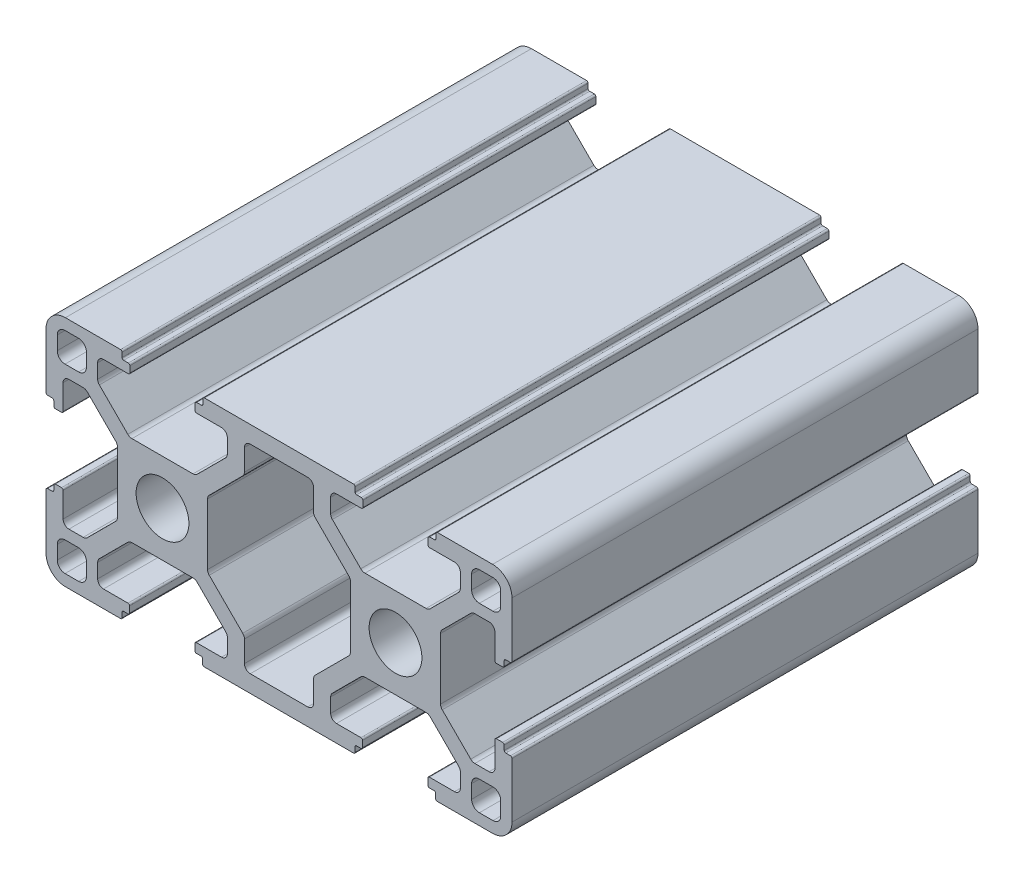
SolidWorks part; units mm, degrees
material "6063-T5"
ref_plane "Front Plane" through (0, 0, 0) normal (0, 0, 1) x (1, 0, 0)
ref_plane "Top Plane" through (0, 0, 0) normal (0, 1, 0) x (1, 0, 0)
ref_plane "Right Plane" through (0, 0, 0) normal (1, 0, 0) x (0, 0, -1)
sketch "Sketch1" plane through (0, 0, 0) normal (0, 0, 1) x (1, 0, 0)
  line L0 (2.5, 0) -> (9.6, 0)
  line L1 (60, 2.5) -> (60, 9.6)
  line L2 (57.5, 30) -> (50.4, 30)
  line L3 (0, 27.5) -> (0, 20.4)
  line L4 (21.0197, 10.536) -> (25.3303, 6.2253)
  line L5 (19.464, 21.0197) -> (23.1303, 24.686)
  line L6 (19.464, 8.9803) -> (23.1303, 5.314)
  line L7 (21.0197, 19.464) -> (25.3303, 23.7747)
  line L8 (11.0663, 9.2) -> (18.9337, 9.2)
  line L9 (9.2, 18.9337) -> (9.2, 11.0663)
  line L10 (41.0663, 9.2) -> (48.9337, 9.2)
  line L11 (40.536, 21.0197) -> (36.8697, 24.686)
  line L12 (50.8, 18.9337) -> (50.8, 11.0663)
  line L13 (38.9803, 10.536) -> (34.6697, 6.2253)
  line L14 (5.314, 23.1303) -> (8.9803, 19.464)
  line L15 (6.8697, 24.686) -> (10.536, 21.0197)
  line L16 (40.536, 8.9803) -> (36.8697, 5.314)
  line L17 (38.9803, 19.464) -> (34.6697, 23.7747)
  line L18 (5.314, 6.8697) -> (8.9803, 10.536)
  line L19 (6.8697, 5.314) -> (10.536, 8.9803)
  line L20 (36.65, 25.2163) -> (36.65, 27.05)
  line L21 (4.7837, 23.35) -> (2.95, 23.35)
  line L22 (4.7837, 6.65) -> (2.95, 6.65)
  line L23 (53.35, 25.2163) -> (53.35, 27.05)
  line L24 (53.1303, 24.686) -> (49.464, 21.0197)
  line L25 (54.686, 23.1303) -> (51.0197, 19.464)
  line L26 (54.686, 6.8697) -> (51.0197, 10.536)
  line L27 (53.1303, 5.314) -> (49.464, 8.9803)
  line L28 (11.0663, 20.8) -> (18.9337, 20.8)
  line L29 (41.0663, 20.8) -> (48.9337, 20.8)
  line L30 (20.8, 18.9337) -> (20.8, 11.0663)
  line L31 (39.2, 18.9337) -> (39.2, 11.0663)
  line L32 (6.65, 4.7837) -> (6.65, 2.95)
  line L33 (6.65, 27.05) -> (6.65, 25.2163)
  line L34 (23.35, 27.05) -> (23.35, 25.2163)
  line L35 (55.2163, 23.35) -> (57.05, 23.35)
  line L36 (55.2163, 6.65) -> (57.05, 6.65)
  line L37 (23.35, 4.7837) -> (23.35, 2.95)
  line L38 (36.65, 4.7837) -> (36.65, 2.95)
  line L39 (53.35, 4.7837) -> (53.35, 2.95)
  line L40 (34.45, 24.305) -> (34.45, 27.05)
  line L41 (25.55, 24.305) -> (25.55, 27.05)
  line L42 (25.55, 5.695) -> (25.55, 2.95)
  line L43 (34.45, 5.695) -> (34.45, 2.95)
  line L44 (26.3, 27.8) -> (33.7, 27.8)
  line L45 (7.4, 27.8) -> (10.6, 27.8)
  line L46 (7.4, 2.2) -> (10.5556, 2.2)
  line L47 (2.2, 22.6) -> (2.2, 19.4)
  line L48 (57.8, 22.6) -> (57.8, 19.4)
  line L49 (37.4, 27.8) -> (40.6, 27.8)
  line L50 (26.3, 2.2) -> (33.7, 2.2)
  line L51 (37.4, 2.2) -> (40.5556, 2.2)
  line L52 (9.6, 30) -> (2.5, 30)
  line L53 (19.2, 28) -> (19.2, 28.8)
  line L54 (10.7556, 2) -> (10.7556, 1.2)
  line L55 (10.8, 28) -> (10.8, 28.8)
  line L56 (19.4, 27.8) -> (22.6, 27.8)
  line L57 (40.8, 28) -> (40.8, 28.8)
  line L58 (19.1556, 2) -> (19.1556, 1.2)
  line L59 (20.3556, 0) -> (39.6, 0)
  line L60 (19.3556, 2.2) -> (22.6, 2.2)
  line L61 (49.1556, 2) -> (49.1556, 1.2)
  line L62 (40.7556, 2) -> (40.7556, 1.2)
  line L63 (49.2, 28) -> (49.2, 28.8)
  line L64 (49.4, 27.8) -> (52.6, 27.8)
  line L65 (39.6, 30) -> (20.4, 30)
  line L66 (50.3556, 0) -> (57.5, 0)
  line L67 (49.3556, 2.2) -> (52.6, 2.2)
  line L68 (4.2, 24.8) -> (2.45, 24.8)
  line L69 (2, 19.2) -> (1.2, 19.2)
  line L70 (58, 19.2) -> (58.8, 19.2)
  line L71 (2, 10.8) -> (1.2, 10.8)
  line L72 (0, 9.6) -> (0, 2.5)
  line L73 (2.2, 10.6) -> (2.2, 7.4)
  line L74 (5.2, 27.55) -> (5.2, 25.8)
  line L75 (58, 10.8) -> (58.8, 10.8)
  line L76 (60, 20.4) -> (60, 27.5)
  line L77 (57.8, 10.6) -> (57.8, 7.4)
  line L78 (55.8, 28.55) -> (57.55, 28.55)
  line L79 (58.55, 4.2) -> (58.55, 2.45)
  line L80 (4.2, 28.55) -> (2.45, 28.55)
  line L81 (1.45, 25.8) -> (1.45, 27.55)
  line L82 (55.8, 24.8) -> (57.55, 24.8)
  line L83 (1.45, 4.2) -> (1.45, 2.45)
  line L84 (2.45, 5.2) -> (4.2, 5.2)
  line L85 (5.2, 2.45) -> (5.2, 4.2)
  line L86 (54.8, 2.45) -> (54.8, 4.2)
  line L87 (55.8, 5.2) -> (57.55, 5.2)
  line L88 (4.2, 1.45) -> (2.45, 1.45)
  line L89 (58.55, 27.55) -> (58.55, 25.8)
  line L90 (19.4, 29) -> (20, 29)
  line L91 (54.8, 25.8) -> (54.8, 27.55)
  line L92 (57.55, 1.45) -> (55.8, 1.45)
  line L93 (9.8, 29.8) -> (9.8, 29.2)
  line L94 (10, 29) -> (10.6, 29)
  line L95 (20.2, 29.2) -> (20.2, 29.8)
  line L96 (9.8, 0.2) -> (9.8, 0.8)
  line L97 (0.2, 20.2) -> (0.8, 20.2)
  line L98 (1, 20) -> (1, 19.4)
  line L99 (1, 10.6) -> (1, 10)
  line L100 (0.8, 9.8) -> (0.2, 9.8)
  line L101 (10, 1) -> (10.5556, 1)
  line L102 (19.3556, 1) -> (19.9556, 1)
  line L103 (20.1556, 0.8) -> (20.1556, 0.2)
  line L104 (50.2, 29.2) -> (50.2, 29.8)
  line L105 (49.4, 29) -> (50, 29)
  line L106 (39.8, 29.8) -> (39.8, 29.2)
  line L107 (40, 29) -> (40.6, 29)
  line L108 (50.1556, 0.8) -> (50.1556, 0.2)
  line L109 (49.3556, 1) -> (49.9556, 1)
  line L110 (40, 1) -> (40.5556, 1)
  line L111 (39.8, 0.2) -> (39.8, 0.8)
  line L112 (59.8, 20.2) -> (59.2, 20.2)
  line L113 (59, 20) -> (59, 19.4)
  line L114 (59, 10.6) -> (59, 10)
  line L115 (59.2, 9.8) -> (59.8, 9.8)
  circle A0 centre (15, 15) radius 3.4
  circle A1 centre (45, 15) radius 3.4
  arc A2 (55.8, 1.45) -> (54.8, 2.45) centre (55.8, 2.45) cw
  arc A3 (57.55, 1.45) -> (58.55, 2.45) centre (57.55, 2.45) ccw
  arc A4 (57.55, 5.2) -> (58.55, 4.2) centre (57.55, 4.2) cw
  arc A5 (54.8, 4.2) -> (55.8, 5.2) centre (55.8, 4.2) cw
  arc A6 (55.8, 24.8) -> (54.8, 25.8) centre (55.8, 25.8) cw
  arc A7 (58.55, 25.8) -> (57.55, 24.8) centre (57.55, 25.8) cw
  arc A8 (57.55, 28.55) -> (58.55, 27.55) centre (57.55, 27.55) cw
  arc A9 (55.8, 28.55) -> (54.8, 27.55) centre (55.8, 27.55) ccw
  arc A10 (4.2, 5.2) -> (5.2, 4.2) centre (4.2, 4.2) cw
  arc A11 (4.2, 1.45) -> (5.2, 2.45) centre (4.2, 2.45) ccw
  arc A12 (2.45, 1.45) -> (1.45, 2.45) centre (2.45, 2.45) cw
  arc A13 (2.45, 5.2) -> (1.45, 4.2) centre (2.45, 4.2) ccw
  arc A14 (2.45, 24.8) -> (1.45, 25.8) centre (2.45, 25.8) cw
  arc A15 (4.2, 28.55) -> (5.2, 27.55) centre (4.2, 27.55) cw
  arc A16 (4.2, 24.8) -> (5.2, 25.8) centre (4.2, 25.8) ccw
  arc A17 (2.45, 28.55) -> (1.45, 27.55) centre (2.45, 27.55) ccw
  arc A18 (60, 27.5) -> (57.5, 30) centre (57.5, 27.5) ccw
  arc A19 (57.5, 0) -> (60, 2.5) centre (57.5, 2.5) ccw
  arc A20 (2.5, 0) -> (0, 2.5) centre (2.5, 2.5) cw
  arc A21 (2.5, 30) -> (0, 27.5) centre (2.5, 27.5) ccw
  arc A22 (53.35, 4.7837) -> (53.1303, 5.314) centre (52.6, 4.7837) ccw
  arc A23 (52.6, 2.2) -> (53.35, 2.95) centre (52.6, 2.95) ccw
  arc A24 (36.65, 2.95) -> (37.4, 2.2) centre (37.4, 2.95) ccw
  arc A25 (36.65, 4.7837) -> (36.8697, 5.314) centre (37.4, 4.7837) cw
  arc A26 (48.9337, 9.2) -> (49.464, 8.9803) centre (48.9337, 8.45) cw
  arc A27 (41.0663, 9.2) -> (40.536, 8.9803) centre (41.0663, 8.45) ccw
  arc A28 (57.8, 7.4) -> (57.05, 6.65) centre (57.05, 7.4) cw
  arc A29 (55.2163, 6.65) -> (54.686, 6.8697) centre (55.2163, 7.4) cw
  arc A30 (50.8, 11.0663) -> (51.0197, 10.536) centre (51.55, 11.0663) ccw
  arc A31 (50.8, 18.9337) -> (51.0197, 19.464) centre (51.55, 18.9337) cw
  arc A32 (55.2163, 23.35) -> (54.686, 23.1303) centre (55.2163, 22.6) ccw
  arc A33 (57.8, 22.6) -> (57.05, 23.35) centre (57.05, 22.6) ccw
  arc A34 (52.6, 27.8) -> (53.35, 27.05) centre (52.6, 27.05) cw
  arc A35 (53.35, 25.2163) -> (53.1303, 24.686) centre (52.6, 25.2163) cw
  arc A36 (48.9337, 20.8) -> (49.464, 21.0197) centre (48.9337, 21.55) ccw
  arc A37 (41.0663, 20.8) -> (40.536, 21.0197) centre (41.0663, 21.55) cw
  arc A38 (36.65, 25.2163) -> (36.8697, 24.686) centre (37.4, 25.2163) ccw
  arc A39 (36.65, 27.05) -> (37.4, 27.8) centre (37.4, 27.05) cw
  arc A40 (23.35, 2.95) -> (22.6, 2.2) centre (22.6, 2.95) cw
  arc A41 (23.35, 4.7837) -> (23.1303, 5.314) centre (22.6, 4.7837) ccw
  arc A42 (18.9337, 9.2) -> (19.464, 8.9803) centre (18.9337, 8.45) cw
  arc A43 (11.0663, 9.2) -> (10.536, 8.9803) centre (11.0663, 8.45) ccw
  arc A44 (6.65, 4.7837) -> (6.8697, 5.314) centre (7.4, 4.7837) cw
  arc A45 (7.4, 2.2) -> (6.65, 2.95) centre (7.4, 2.95) cw
  arc A46 (34.45, 27.05) -> (33.7, 27.8) centre (33.7, 27.05) ccw
  arc A47 (34.45, 24.305) -> (34.6697, 23.7747) centre (35.2, 24.305) ccw
  arc A48 (39.2, 18.9337) -> (38.9803, 19.464) centre (38.45, 18.9337) ccw
  arc A49 (39.2, 11.0663) -> (38.9803, 10.536) centre (38.45, 11.0663) cw
  arc A50 (34.45, 5.695) -> (34.6697, 6.2253) centre (35.2, 5.695) cw
  arc A51 (34.45, 2.95) -> (33.7, 2.2) centre (33.7, 2.95) cw
  arc A52 (25.55, 2.95) -> (26.3, 2.2) centre (26.3, 2.95) ccw
  arc A53 (25.55, 5.695) -> (25.3303, 6.2253) centre (24.8, 5.695) ccw
  arc A54 (20.8, 11.0663) -> (21.0197, 10.536) centre (21.55, 11.0663) ccw
  arc A55 (20.8, 18.9337) -> (21.0197, 19.464) centre (21.55, 18.9337) cw
  arc A56 (25.55, 24.305) -> (25.3303, 23.7747) centre (24.8, 24.305) cw
  arc A57 (25.55, 27.05) -> (26.3, 27.8) centre (26.3, 27.05) cw
  arc A58 (23.35, 27.05) -> (22.6, 27.8) centre (22.6, 27.05) ccw
  arc A59 (23.35, 25.2163) -> (23.1303, 24.686) centre (22.6, 25.2163) cw
  arc A60 (18.9337, 20.8) -> (19.464, 21.0197) centre (18.9337, 21.55) ccw
  arc A61 (11.0663, 20.8) -> (10.536, 21.0197) centre (11.0663, 21.55) cw
  arc A62 (6.65, 25.2163) -> (6.8697, 24.686) centre (7.4, 25.2163) ccw
  arc A63 (7.4, 27.8) -> (6.65, 27.05) centre (7.4, 27.05) ccw
  arc A64 (2.2, 7.4) -> (2.95, 6.65) centre (2.95, 7.4) ccw
  arc A65 (4.7837, 6.65) -> (5.314, 6.8697) centre (4.7837, 7.4) ccw
  arc A66 (9.2, 11.0663) -> (8.9803, 10.536) centre (8.45, 11.0663) cw
  arc A67 (9.2, 18.9337) -> (8.9803, 19.464) centre (8.45, 18.9337) ccw
  arc A68 (4.7837, 23.35) -> (5.314, 23.1303) centre (4.7837, 22.6) cw
  arc A69 (2.2, 22.6) -> (2.95, 23.35) centre (2.95, 22.6) cw
  arc A70 (49.2, 28) -> (49.4, 27.8) centre (49.4, 28) ccw
  arc A71 (49.4, 29) -> (49.2, 28.8) centre (49.4, 28.8) ccw
  arc A72 (50.2, 29.2) -> (50, 29) centre (50, 29.2) cw
  arc A73 (50.2, 29.8) -> (50.4, 30) centre (50.4, 29.8) cw
  arc A74 (59.8, 20.2) -> (60, 20.4) centre (59.8, 20.4) ccw
  arc A75 (59.2, 20.2) -> (59, 20) centre (59.2, 20) ccw
  arc A76 (59, 19.4) -> (58.8, 19.2) centre (58.8, 19.4) cw
  arc A77 (57.8, 19.4) -> (58, 19.2) centre (58, 19.4) ccw
  arc A78 (57.8, 10.6) -> (58, 10.8) centre (58, 10.6) cw
  arc A79 (59, 10.6) -> (58.8, 10.8) centre (58.8, 10.6) ccw
  arc A80 (59, 10) -> (59.2, 9.8) centre (59.2, 10) ccw
  arc A81 (59.8, 9.8) -> (60, 9.6) centre (59.8, 9.6) cw
  arc A82 (50.1556, 0.2) -> (50.3556, 0) centre (50.3556, 0.2) ccw
  arc A83 (50.1556, 0.8) -> (49.9556, 1) centre (49.9556, 0.8) ccw
  arc A84 (49.3556, 1) -> (49.1556, 1.2) centre (49.3556, 1.2) cw
  arc A85 (49.1556, 2) -> (49.3556, 2.2) centre (49.3556, 2) cw
  arc A86 (39.8, 0.2) -> (39.6, 0) centre (39.6, 0.2) cw
  arc A87 (40, 1) -> (39.8, 0.8) centre (40, 0.8) ccw
  arc A88 (40.5556, 1) -> (40.7556, 1.2) centre (40.5556, 1.2) ccw
  arc A89 (40.7556, 2) -> (40.5556, 2.2) centre (40.5556, 2) ccw
  arc A90 (20.1556, 0.2) -> (20.3556, 0) centre (20.3556, 0.2) ccw
  arc A91 (19.9556, 1) -> (20.1556, 0.8) centre (19.9556, 0.8) cw
  arc A92 (19.3556, 1) -> (19.1556, 1.2) centre (19.3556, 1.2) cw
  arc A93 (19.3556, 2.2) -> (19.1556, 2) centre (19.3556, 2) ccw
  arc A94 (9.8, 0.2) -> (9.6, 0) centre (9.6, 0.2) cw
  arc A95 (9.8, 0.8) -> (10, 1) centre (10, 0.8) cw
  arc A96 (10.5556, 1) -> (10.7556, 1.2) centre (10.5556, 1.2) ccw
  arc A97 (10.7556, 2) -> (10.5556, 2.2) centre (10.5556, 2) ccw
  arc A98 (0.2, 9.8) -> (0, 9.6) centre (0.2, 9.6) ccw
  arc A99 (1, 10) -> (0.8, 9.8) centre (0.8, 10) cw
  arc A100 (1.2, 10.8) -> (1, 10.6) centre (1.2, 10.6) ccw
  arc A101 (2.2, 10.6) -> (2, 10.8) centre (2, 10.6) ccw
  arc A102 (2.2, 19.4) -> (2, 19.2) centre (2, 19.4) cw
  arc A103 (1, 19.4) -> (1.2, 19.2) centre (1.2, 19.4) ccw
  arc A104 (0.8, 20.2) -> (1, 20) centre (0.8, 20) cw
  arc A105 (0, 20.4) -> (0.2, 20.2) centre (0.2, 20.4) ccw
  arc A106 (40.8, 28) -> (40.6, 27.8) centre (40.6, 28) cw
  arc A107 (40.6, 29) -> (40.8, 28.8) centre (40.6, 28.8) cw
  arc A108 (39.8, 29.2) -> (40, 29) centre (40, 29.2) ccw
  arc A109 (39.8, 29.8) -> (39.6, 30) centre (39.6, 29.8) ccw
  arc A110 (19.4, 27.8) -> (19.2, 28) centre (19.4, 28) cw
  arc A111 (19.4, 29) -> (19.2, 28.8) centre (19.4, 28.8) ccw
  arc A112 (20, 29) -> (20.2, 29.2) centre (20, 29.2) ccw
  arc A113 (20.2, 29.8) -> (20.4, 30) centre (20.4, 29.8) cw
  arc A114 (10.6, 27.8) -> (10.8, 28) centre (10.6, 28) ccw
  arc A115 (10.6, 29) -> (10.8, 28.8) centre (10.6, 28.8) cw
  arc A116 (9.8, 29.2) -> (10, 29) centre (10, 29.2) ccw
  arc A117 (9.6, 30) -> (9.8, 29.8) centre (9.6, 29.8) cw
  point P135 (0, 0)
extrude "Boss-Extrude1" add sketch "Sketch1" along normal blind 60 contours L52 A21 L3 A105 L97 A104 L98 A103 L69 A102 L47 A69 L21 A68 L14 A67 L9 A66 L18 A65 L22 A64 L73 A101 L71 A100 L99 A99 L100 A98 L72 A20 L0 A94 L96 A95 L101 A96 L54 A97 L46 A45 L32 A44 L19 A43 L8 A42 L6 A41 L37 A40 L60 A93 L58 A92 L102 A91 L103 A90 L59 A86 L111 A87 L110 A88 L62 A89 L51 A24 L38 A25 L16 A27 L10 A26 L27 A22 L39 A23 L67 A85 L61 A84 L109 A83 L108 A82 L66 A19 L1 A81 L115 A80 L114 A79 L75 A78 L77 A28 L36 A29 L26 A30 L12 A31 L25 A32 L35 A33 L48 A77 L70 A76 L113 A75 L112 A74 L76 A18 L2 A73 L104 A72 L105 A71 L63 A70 L64 A34 L23 A35 L24 A36 L29 A37 L11 A38 L20 A39 L49 A106 L57 A107 L107 A108 L106 A109 L65 A113 L95 A112 L90 A111 L53 A110 L56 A58 L34 A59 L5 A60 L28 A61 L15 A62 L33 A63 L45 A114 L55 A115 L94 A116 L93 A117 | A0 | A1 | L41 A57 L44 A46 L40 A47 L17 A48 L31 A49 L13 A50 L43 A51 L50 A52 L42 A53 L4 A54 L30 A55 L7 A56 | L85 A10 L84 A13 L83 A12 L88 A11 | L74 A16 L68 A14 L81 A17 L80 A15 | L89 A7 L82 A6 L91 A9 L78 A8 | L79 A3 L92 A2 L86 A5 L87 A4
